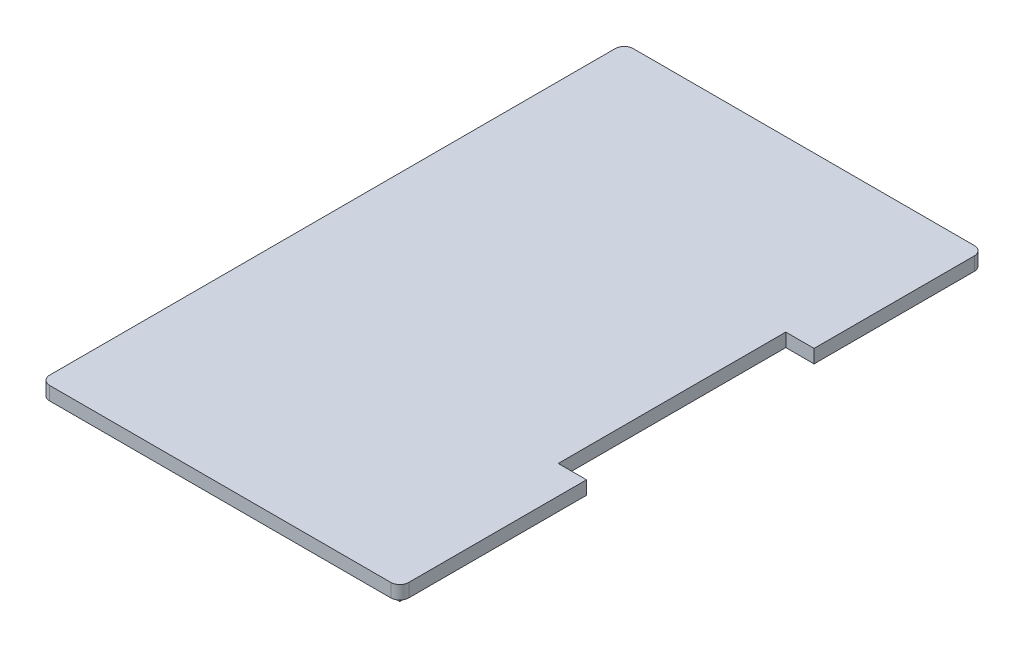
SolidWorks part; units mm, degrees
ref_plane "Front Plane" through (0, 0, 0) normal (0, 0, 1) x (1, 0, 0)
ref_plane "Top Plane" through (0, 0, 0) normal (0, 1, 0) x (1, 0, 0)
ref_plane "Right Plane" through (0, 0, 0) normal (1, 0, 0) x (0, 0, -1)
sketch "Sketch1" plane through (0, 0, 0) normal (0, 1, 0) x (1, 0, 0)
  line L1 (-20.6178, 38.7219) -> (19.3822, 38.7219)
  line L2 (-20.6178, 38.7219) -> (-20.6178, -26.2781)
  line L3 (-20.6178, -26.2781) -> (19.3822, -26.2781)
  line L4 (19.3822, 38.7219) -> (19.3822, -26.2781)
  line L5 (19.3822, 19.8719) -> (16.2322, 19.8719)
  line L6 (19.3822, 19.8719) -> (19.3822, -5.4781)
  line L7 (19.3822, -5.4781) -> (16.2322, -5.4781)
  line L8 (16.2322, 19.8719) -> (16.2322, -5.4781)
  dimension "D1" = 40
  dimension "D2" = 65
  dimension "D3" = 18.85
  dimension "D4" = 25.35
  dimension "D5" = 3.15
extrude "Boss-Extrude1" add sketch "Sketch1" along normal blind 1.5 contours L8 L5 L4 L1 L2 L3 L7
sketch "Sketch2" plane through (0, 0, 0) normal (0, -1, 0) x (1, 0, 0)
  line L0 (-18.9678, 24.6281) -> (17.7322, 24.6281)
  line L5 (17.7322, 24.6281) -> (17.7322, 7.1281)
  line L6 (17.7322, 7.1281) -> (14.5822, 7.1281)
  line L7 (14.5822, 7.1281) -> (14.5822, -21.5219)
  line L8 (14.5822, -21.5219) -> (17.7322, -21.5219)
  line L9 (17.7322, -21.5219) -> (17.7322, -37.0719)
  line L10 (17.7322, -37.0719) -> (-18.9678, -37.0719)
  line L11 (-18.9678, -37.0719) -> (-18.9678, 24.6281)
  line L12 (-20.6178, 26.2781) -> (19.3822, 26.2781) construction
  line L13 (19.3822, 5.4781) -> (19.3822, 26.2781) construction
  line L14 (-20.6178, -38.7219) -> (-20.6178, 26.2781) construction
  line L15 (-20.6178, -38.7219) -> (19.3822, -38.7219) construction
  line L16 (19.3822, -38.7219) -> (19.3822, -19.8719) construction
  line L17 (16.2322, -19.8719) -> (16.2322, 5.4781) construction
  line L18 (19.3822, -19.8719) -> (16.2322, -19.8719) construction
  line L19 (19.3822, 5.4781) -> (16.2322, 5.4781) construction
  line L20 (-17.4678, 23.1281) -> (-17.4678, -35.5719)
  line L21 (-17.4678, -35.5719) -> (16.2322, -35.5719)
  line L22 (16.2322, -35.5719) -> (16.2322, -23.0219)
  line L23 (16.2322, -23.0219) -> (13.0822, -23.0219)
  line L24 (13.0822, -23.0219) -> (13.0822, 8.6281)
  line L25 (13.0822, 8.6281) -> (16.2322, 8.6281)
  line L26 (16.2322, 8.6281) -> (16.2322, 23.1281)
  line L27 (16.2322, 23.1281) -> (-17.4678, 23.1281)
  point P22 (17.8072, -19.8719)
  dimension "D1" = 1.65
  dimension "D2" = 1.65
  dimension "D3" = 1.65
  dimension "D4" = 1.65
  dimension "D5" = 1.65
  dimension "D6" = 1.65
  dimension "D7" = 1.65
  dimension "D8" = 1.65
  dimension "D9" = 1.5
  dimension "D10" = 1.5
  dimension "D11" = 1.5
  dimension "D12" = 1.5
  dimension "D13" = 1.5
  dimension "D14" = 1.5
  dimension "D15" = 1.5
  dimension "D16" = 1.5
extrude "Boss-Extrude2" add sketch "Sketch2" along normal blind 1.5
fillet "Fillet1" radius 1 4 edges at (19.3822, 0.75, -38.7219) (-20.6178, 0.75, 26.2781) (-20.6178, 0.75, -38.7219) (19.3822, 0.75, 26.2781)
